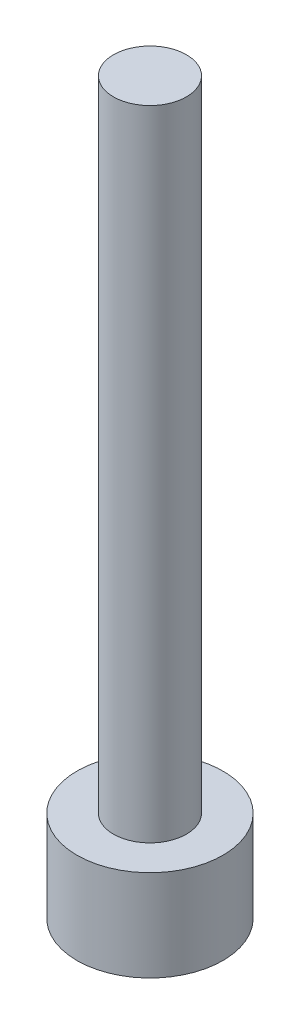
SolidWorks part; units mm, degrees
ref_plane "Front Plane" through (0, 0, 0) normal (0, 0, 1) x (1, 0, 0)
ref_plane "Top Plane" through (0, 0, 0) normal (0, 1, 0) x (1, 0, 0)
ref_plane "Right Plane" through (0, 0, 0) normal (1, 0, 0) x (0, 0, -1)
sketch "Sketch1" plane through (0, 0, 0) normal (0, 1, 0) x (1, 0, 0)
  circle A0 centre (0, 0) radius 4
extrude "Boss-Extrude2" add sketch "Sketch1" along normal blind 5
sketch "Sketch2" plane through (0, 5, 0) normal (0, 1, 0) x (1, 0, 0)
  circle A0 centre (0, 0) radius 2
extrude "Boss-Extrude3" add sketch "Sketch2" along normal blind 35
